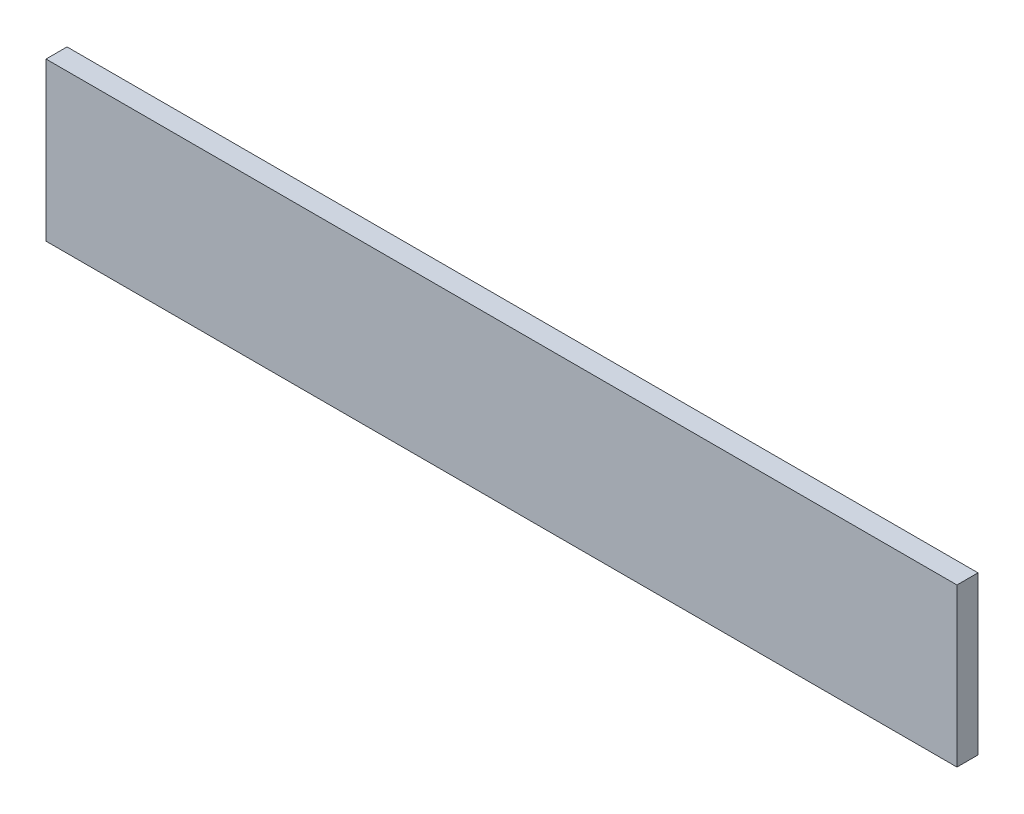
SolidWorks part; units mm, degrees
material "Q235A"
ref_plane "前视" through (0, 0, 0) normal (0, 0, 1) x (1, 0, 0)
ref_plane "上视" through (0, 0, 0) normal (0, 1, 0) x (1, 0, 0)
ref_plane "右视" through (0, 0, 0) normal (1, 0, 0) x (0, 0, -1)
sketch "草图1" plane through (0, 0, 0) normal (0, 0, 1) x (1, 0, 0)
  line L1 (346.5, -60) -> (-346.5, -60)
  line L2 (346.5, -60) -> (346.5, 60)
  line L3 (346.5, 60) -> (-346.5, 60)
  line L4 (-346.5, -60) -> (-346.5, 60)
  line L5 (346.5, -60) -> (-346.5, 60) construction
  line L6 (346.5, 60) -> (-346.5, -60) construction
  point P0 (0, 0)
  dimension "D1" = 120
  dimension "D2" = 693
extrude "凸台-拉伸1" add sketch "草图1" along normal blind 16
